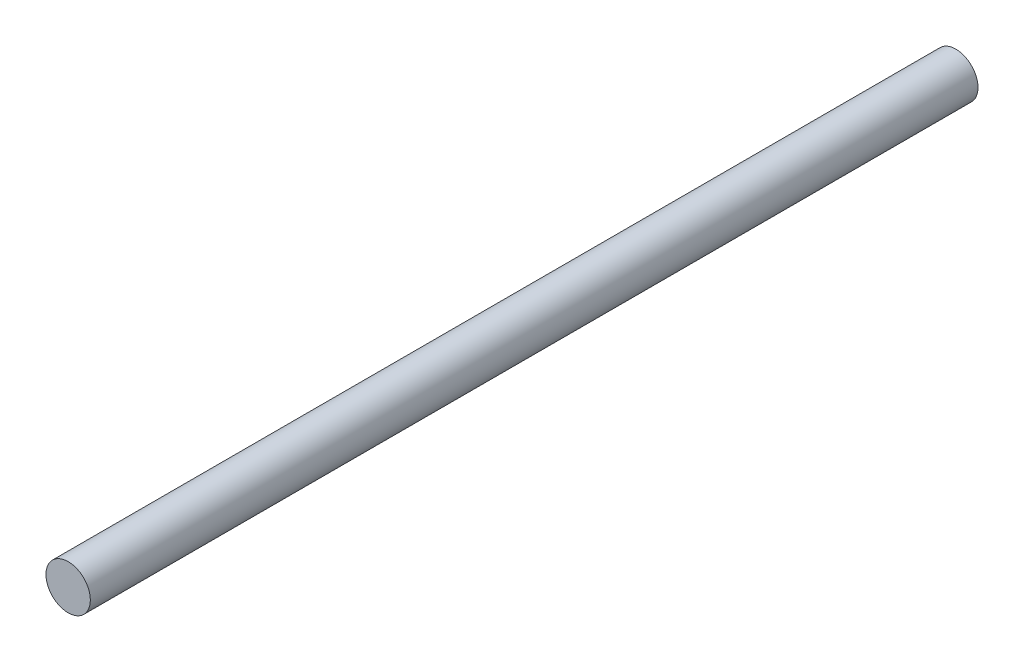
SolidWorks part; units mm, degrees
ref_plane "Alzado" through (0, 0, 0) normal (0, 0, 1) x (1, 0, 0)
ref_plane "Planta" through (0, 0, 0) normal (0, 1, 0) x (1, 0, 0)
ref_plane "Vista lateral" through (0, 0, 0) normal (1, 0, 0) x (0, 0, -1)
sketch "Croquis1" plane through (0, 0, 0) normal (0, 0, 1) x (1, 0, 0)
  circle A0 centre (0, 0) radius 2.5
extrude "Saliente-Extruir1" add sketch "Croquis1" against normal blind 100
